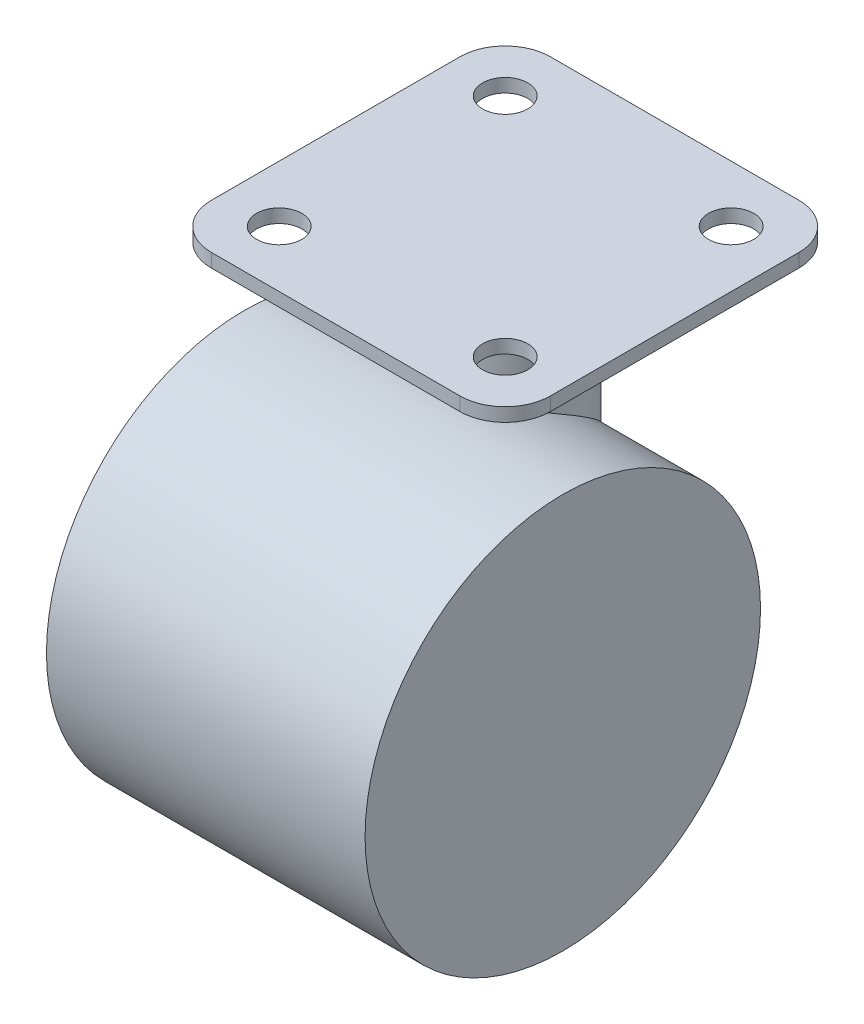
SolidWorks part; units mm, degrees
ref_plane "Спереди" through (0, 0, 0) normal (0, 0, 1) x (1, 0, 0)
ref_plane "Сверху" through (0, 0, 0) normal (0, 1, 0) x (1, 0, 0)
ref_plane "Справа" through (0, 0, 0) normal (1, 0, 0) x (0, 0, -1)
sketch "Эскиз1" plane through (0, 0, 0) normal (0, 1, 0) x (1, 0, 0)
  line L1 (-15, -15) -> (15, -15)
  line L2 (-15, -15) -> (-15, 15)
  line L3 (-15, 15) -> (15, 15)
  line L4 (15, -15) -> (15, 15)
  line L5 (-15, -15) -> (15, 15) construction
  line L6 (-15, 15) -> (15, -15) construction
  point P0 (0, 0)
  dimension "D2" = 30
extrude "основание" add sketch "Эскиз1" against normal mid plane 1.2
sketch "Эскиз7" plane through (0, 0.6, 0) normal (0, 1, 0) x (1, 0, 0)
  line L1 (-10, -10) -> (10, -10) construction
  line L2 (-10, -10) -> (-10, 10) construction
  line L3 (-10, 10) -> (10, 10) construction
  line L4 (10, -10) -> (10, 10) construction
  line L5 (-10, -10) -> (10, 10) construction
  line L6 (-10, 10) -> (10, -10) construction
  circle A0 centre (-10, 10) radius 2
  circle A1 centre (10, 10) radius 2
  circle A2 centre (10, -10) radius 2
  circle A3 centre (-10, -10) radius 2
  point P0 (0, 0)
  dimension "D1" = 4
  dimension "D2" = 20
  dimension "D3" = 20
extrude "крепженые отверстия" cut sketch "Эскиз7" against normal through all
fillet "Скругление4" radius 4 4 edges at (15, 0, -15) (15, 0, 15) (-15, 0, 15) (-15, 0, -15)
sketch "Эскиз9" plane through (0, 0, 0) normal (1, 0, 0) x (0, 0, -1)
  line L1 (-11, 0.6) -> (11, 0.6) construction
  circle A0 centre (-9, -25.9) radius 17.5
  point P5 (-9, -43.4)
  dimension "D1" = 35
  dimension "D3" = 9
  dimension "D2" = 44
extrude "Колесо" add sketch "Эскиз9" along normal mid plane 28.2 separate body
sketch "Эскиз8" plane through (0, -0.6, 0) normal (0, -1, 0) x (1, 0, 0)
  circle A0 centre (0, 0) radius 6
  dimension "D1" = 12
extrude "Штырь" add sketch "Эскиз8" along normal up to surface (16.2861 mm away)
